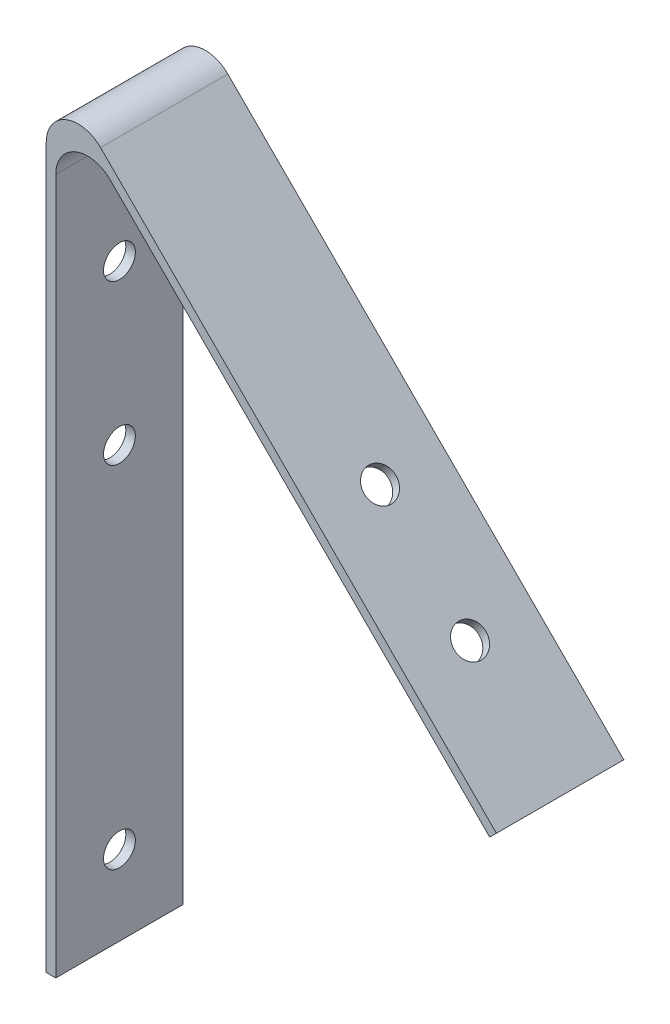
SolidWorks part; units mm, degrees
ref_plane "Front Plane" through (0, 0, 0) normal (0, 0, 1) x (1, 0, 0)
ref_plane "Top Plane" through (0, 0, 0) normal (0, 1, 0) x (1, 0, 0)
ref_plane "Right Plane" through (0, 0, 0) normal (1, 0, 0) x (0, 0, -1)
sketch "Sketch1" plane through (0, 0, 0) normal (0, 0, 1) x (1, 0, 0)
  line L0 (0, 0) -> (0, 225.8579)
  line L1 (17.0711, 232.9289) -> (141.4214, 108.5786)
  line L2 (141.4214, 108.5786) -> (139.3, 106.4573)
  line L3 (139.3, 106.4573) -> (20.0711, 225.6863)
  line L4 (3, 218.6152) -> (3, 0)
  line L5 (3, 0) -> (0, 0)
  arc A0 (20.0711, 225.6863) -> (3, 218.6152) centre (13, 218.6152) ccw
  arc A1 (17.0711, 232.9289) -> (0, 225.8579) centre (10, 225.8579) ccw
  point P11 (0, 250)
  dimension "D6" = 10
  dimension "D1" = 3
  dimension "D2" = 3
  dimension "D3" = 45
  dimension "D4" = 250
  dimension "D5" = 200
extrude "Boss-Extrude1" add sketch "Sketch1" along normal blind 40
sketch "Sketch2" plane through (3, 0, 0) normal (1, 0, 0) x (0, 0, -1)
  line L0 (-40, 0) -> (-40, 218.6152) construction
  line L1 (-40, 0) -> (0, 0) construction
  circle A0 centre (-20, 185) radius 5
  circle A1 centre (-20, 25) radius 5
  circle A2 centre (-20, 135) radius 5
  dimension "D1" = 10
  dimension "D2" = 10
  dimension "D6" = 10
  dimension "D3" = 20
  dimension "D4" = 160
  dimension "D5" = 25
  dimension "D7" = 50
extrude "Cut-Extrude1" cut sketch "Sketch2" against normal blind 40
sketch "Sketch3" plane through (125, 125, 0) normal (0.7071, 0.7071, 0) x (0, 0, -1)
  line L0 (-40, -23.2233) -> (-40, 152.6346) construction
  line L1 (-40, -23.2233) -> (0, -23.2233) construction
  circle A0 centre (-20, 16.7767) radius 5
  circle A1 centre (-20, 56.7767) radius 5
  dimension "D2" = 10
  dimension "D3" = 10
  dimension "D1" = 20
  dimension "D4" = 40
  dimension "D5" = 40
extrude "Cut-Extrude2" cut sketch "Sketch3" against normal blind 40
